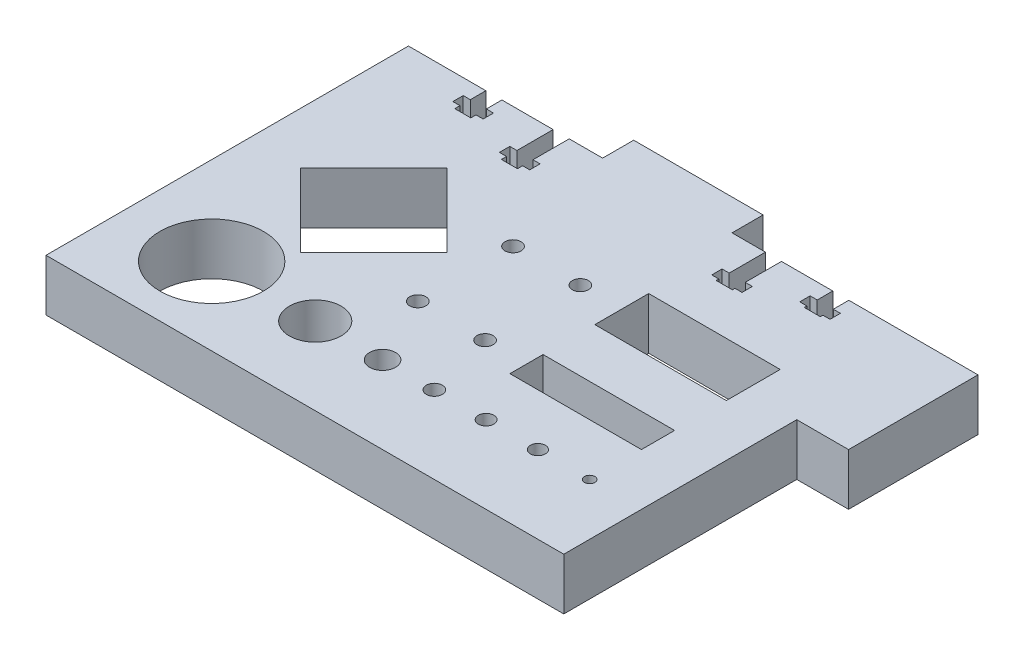
SolidWorks part; units mm, degrees
ref_plane "Płaszczyzna przednia" through (0, 0, 0) normal (0, 0, 1) x (1, 0, 0)
ref_plane "Płaszczyzna górna" through (0, 0, 0) normal (0, 1, 0) x (1, 0, 0)
ref_plane "Płaszczyzna prawa" through (0, 0, 0) normal (1, 0, 0) x (0, 0, -1)
sketch "Szkic1" plane through (0, 0, 0) normal (0, 1, 0) x (1, 0, 0)
  line L0 (208.4263, -256.0776) -> (233.3763, -256.0776)
  line L1 (223.3763, -281.0776) -> (223.3763, -326.0776)
  line L3 (223.3763, -326.0776) -> (123.3763, -326.0776)
  line L5 (213.3763, -294.6776) -> (187.9763, -294.6776)
  line L6 (123.3763, -326.0776) -> (123.3763, -256.0776)
  line L7 (195.4263, -256.0776) -> (205.3263, -256.0776)
  line L8 (223.3763, -281.0776) -> (233.3763, -281.0776)
  line L9 (233.3763, -256.0776) -> (233.3763, -281.0776)
  line L10 (213.3763, -294.6776) -> (213.3763, -301.0776)
  line L11 (187.9763, -294.6776) -> (187.9763, -301.0776)
  line L12 (213.3763, -301.0776) -> (187.9763, -301.0776)
  line L13 (213.3763, -274.2776) -> (187.9763, -274.2776)
  line L14 (213.3763, -274.2776) -> (213.3763, -284.6776)
  line L15 (187.9763, -274.2776) -> (187.9763, -284.6776)
  line L16 (213.3763, -284.6776) -> (187.9763, -284.6776)
  line L17 (161.6606, -286.9354) -> (147.5184, -272.7933)
  line L18 (161.6606, -286.9354) -> (147.5184, -301.0776)
  line L19 (147.5184, -272.7933) -> (133.3763, -286.9354)
  line L20 (147.5184, -301.0776) -> (133.3763, -286.9354)
  line L21 (208.4263, -256.0776) -> (208.4263, -259.0776)
  line L22 (195.4263, -256.0776) -> (195.4263, -263.0776)
  line L23 (192.3263, -256.0776) -> (192.3263, -263.0776)
  line L24 (195.4263, -265.5776) -> (192.3263, -265.5776)
  line L25 (196.8013, -263.0776) -> (195.4263, -263.0776)
  line L26 (196.8013, -263.0776) -> (196.8013, -265.0776)
  line L27 (190.9513, -263.0776) -> (190.9513, -265.0776)
  line L28 (196.8013, -265.0776) -> (195.4263, -265.0776)
  line L29 (195.4263, -265.0776) -> (195.4263, -265.5776)
  line L30 (192.3263, -263.0776) -> (190.9513, -263.0776)
  line L31 (192.3263, -265.0776) -> (190.9513, -265.0776)
  line L32 (192.3263, -265.0776) -> (192.3263, -265.5776)
  line L33 (192.3263, -256.0776) -> (185.8763, -256.0776)
  line L34 (205.3263, -256.0776) -> (205.3263, -259.0776)
  line L35 (208.4263, -261.5776) -> (205.3263, -261.5776)
  line L36 (209.8013, -259.0776) -> (208.4263, -259.0776)
  line L37 (209.8013, -259.0776) -> (209.8013, -261.0776)
  line L38 (203.9513, -259.0776) -> (203.9513, -261.0776)
  line L39 (209.8013, -261.0776) -> (208.4263, -261.0776)
  line L40 (208.4263, -261.0776) -> (208.4263, -261.5776)
  line L41 (205.3263, -259.0776) -> (203.9513, -259.0776)
  line L42 (205.3263, -261.0776) -> (205.3263, -261.5776)
  line L43 (205.3263, -261.0776) -> (203.9513, -261.0776)
  line L44 (185.8763, -256.0776) -> (185.8763, -250.0776)
  line L45 (151.3263, -256.0776) -> (141.4263, -256.0776)
  line L46 (185.8763, -250.0776) -> (160.8763, -250.0776)
  line L47 (160.8763, -256.0776) -> (160.8763, -250.0776)
  line L48 (160.8763, -256.0776) -> (154.4263, -256.0776)
  line L49 (154.4263, -256.0776) -> (154.4263, -263.0776)
  line L50 (151.3263, -256.0776) -> (151.3263, -263.0776)
  line L51 (154.4263, -266.0776) -> (151.3263, -266.0776)
  line L52 (155.8013, -263.0776) -> (154.4263, -263.0776)
  line L53 (155.8013, -263.0776) -> (155.8013, -265.0776)
  line L54 (149.9513, -263.0776) -> (149.9513, -265.0776)
  line L55 (155.8013, -265.0776) -> (154.4263, -265.0776)
  line L56 (151.3263, -263.0776) -> (149.9513, -263.0776)
  line L57 (151.3263, -265.0776) -> (149.9513, -265.0776)
  line L58 (151.3263, -265.0776) -> (151.3263, -266.0776)
  line L59 (154.4263, -265.0776) -> (154.4263, -266.0776)
  line L61 (141.4263, -256.0776) -> (141.4263, -259.0776)
  line L62 (138.3263, -256.0776) -> (138.3263, -259.0776)
  line L63 (141.4263, -262.0776) -> (138.3263, -262.0776)
  line L64 (142.8013, -259.0776) -> (141.4263, -259.0776)
  line L65 (142.8013, -259.0776) -> (142.8013, -261.0776)
  line L66 (136.9513, -259.0776) -> (136.9513, -261.0776)
  line L67 (142.8013, -261.0776) -> (141.4263, -261.0776)
  line L68 (141.4263, -261.0776) -> (141.4263, -262.0776)
  line L69 (138.3263, -259.0776) -> (136.9513, -259.0776)
  line L70 (138.3263, -261.0776) -> (136.9513, -261.0776)
  line L71 (138.3263, -261.0776) -> (138.3263, -262.0776)
  line L72 (138.3263, -256.0776) -> (123.3763, -256.0776)
  circle A0 centre (213.3763, -311.0776) radius 1
  circle A1 centre (193.3763, -311.0776) radius 1.5
  circle A2 centre (183.3763, -311.0776) radius 1.55
  circle A3 centre (173.3763, -311.0776) radius 2.5
  circle A4 centre (160.3763, -311.0776) radius 5
  circle A5 centre (140.3763, -311.0776) radius 10
  circle A6 centre (179.9763, -279.4776) radius 1.55
  circle A7 centre (166.9763, -279.4776) radius 1.55
  circle A8 centre (179.9763, -297.8776) radius 1.55
  circle A9 centre (166.9763, -297.8776) radius 1.55
  circle A10 centre (203.3763, -311.0776) radius 1.45
  point P57 (206.8763, -261.5776)
  point P58 (193.8763, -265.5776)
  point P75 (152.8763, -266.0776)
  point P88 (139.8763, -262.0776)
  point P93 (173.3763, -250.0776)
  dimension "D3" = 2
  dimension "D4" = 3
  dimension "D5" = 3.1
  dimension "D6" = 5
  dimension "D7" = 10
  dimension "D8" = 2.9
  dimension "D9" = 10
  dimension "D10" = 10
  dimension "D11" = 13
  dimension "D13" = 15
  dimension "D27" = 20
  dimension "D28" = 0
  dimension "D32" = 20
  dimension "D25" = 13
  dimension "D26" = 8
  dimension "D31" = 13
  dimension "D63" = 3.1
  dimension "D64" = 3.1
  dimension "D65" = 3.1
  dimension "D66" = 3.1
  dimension "D15" = 10
  dimension "D72" = 10
  dimension "D74" = 5.2
  dimension "D75" = 0
  dimension "D76" = 3.2
  dimension "D12" = 10
  dimension "D14" = 100
  dimension "D16" = 25
  dimension "D17" = 10
  dimension "D18" = 6.4
  dimension "D19" = 25.4
  dimension "D20" = 10.4
  dimension "D21" = 25.4
  dimension "D22" = 10
  dimension "D23" = 10
  dimension "D24" = 8
  dimension "D29" = 10
  dimension "D30" = 25
  dimension "D33" = 3.1
  dimension "D34" = 5.85
  dimension "D35" = 1.375
  dimension "D36" = 0.5
  dimension "D37" = 2
  dimension "D38" = 9.5
  dimension "D40" = 2
  dimension "D39" = 5.5
  dimension "D41" = 3.1
  dimension "D42" = 0.5
  dimension "D43" = 1.375
  dimension "D44" = 5.85
  dimension "D45" = 13
  dimension "D46" = 6
  dimension "D47" = 8
  dimension "D48" = 25
  dimension "D49" = 3.1
  dimension "D50" = 1.375
  dimension "D51" = 2
  dimension "D52" = 1
  dimension "D53" = 5.85
  dimension "D54" = 10
  dimension "D55" = 8
  dimension "D56" = 3.1
  dimension "D57" = 5.85
  dimension "D58" = 1.375
  dimension "D59" = 2
  dimension "D60" = 6
  dimension "D61" = 1
  dimension "D62" = 13
  dimension "D67" = 20
  dimension "D68" = 20
  dimension "D69" = 45
  dimension "D70" = 10
  dimension "D71" = 70
  dimension "D73" = 50
  dimension "D77" = 25
extrude "Dodanie-wyciągnięcie1" add sketch "Szkic1" along normal blind 10
equation "\"tolerancja_wpusy\"=0.2"
equation "\"dlugosc_wpustu_duzy\"=20"
equation "\"srednica_otworu_M3\"=3.1"
equation "\"szerokosc_nogi_T\"=3.1"
equation "\"dlugosc_T_30\"=11"
equation "\"grubosc_na_nakretke_kwadrat\"=2"
equation "\"szerokosc_na_nakretke_kwadrat\"=5.85"
equation "\"wyokosc_nadstawki_T\"=0.5"
equation "\"dlugosc_T_20_6\"=14"
equation "\"D34@Szkic1\"=\"szerokosc_na_nakretke_kwadrat\""
equation "\"D33@Szkic1\"=\"szerokosc_nogi_T\""
equation "\"D35@Szkic1\"=(\"szerokosc_na_nakretke_kwadrat\"-\"szerokosc_nogi_T\")/2"
equation "\"D36@Szkic1\"=\"wyokosc_nadstawki_T\""
equation "\"D37@Szkic1\"=\"grubosc_na_nakretke_kwadrat\""
equation "\"D40@Szkic1\"=\"grubosc_na_nakretke_kwadrat\""
equation "\"D41@Szkic1\"=\"szerokosc_nogi_T\""
equation "\"D42@Szkic1\"=\"wyokosc_nadstawki_T\""
equation "\"D43@Szkic1\"=(\"szerokosc_na_nakretke_kwadrat\"-\"szerokosc_nogi_T\")/2"
equation "\"D44@Szkic1\"=\"szerokosc_na_nakretke_kwadrat\""
equation "\"D49@Szkic1\"=\"szerokosc_nogi_T\""
equation "\"D50@Szkic1\"=(\"szerokosc_na_nakretke_kwadrat\"-\"szerokosc_nogi_T\")/2"
equation "\"D51@Szkic1\"=\"grubosc_na_nakretke_kwadrat\""
equation "\"D53@Szkic1\"=\"szerokosc_na_nakretke_kwadrat\""
equation "\"D56@Szkic1\"=\"szerokosc_nogi_T\""
equation "\"D57@Szkic1\"=\"szerokosc_na_nakretke_kwadrat\""
equation "\"D58@Szkic1\"=(\"szerokosc_na_nakretke_kwadrat\"-\"szerokosc_nogi_T\")/2"
equation "\"D59@Szkic1\"=\"grubosc_na_nakretke_kwadrat\""
equation "\"D63@Szkic1\"=\"srednica_otworu_M3\""
equation "\"D64@Szkic1\"=\"srednica_otworu_M3\""
equation "\"D65@Szkic1\"=\"srednica_otworu_M3\""
equation "\"D66@Szkic1\"=\"srednica_otworu_M3\""
